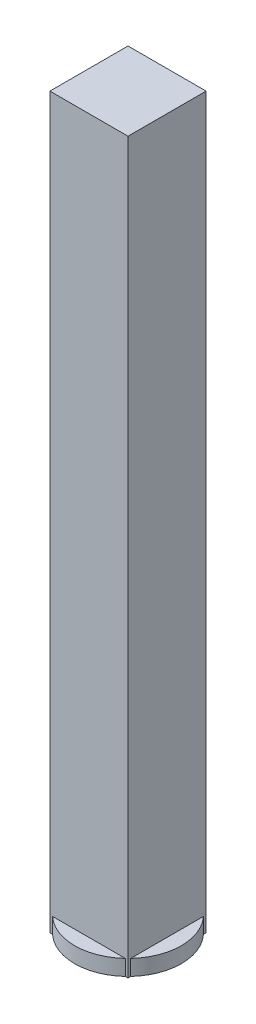
SolidWorks part; units mm, degrees
ref_plane "前视基准面" through (0, 0, 0) normal (0, 0, 1) x (1, 0, 0)
ref_plane "上视基准面" through (0, 0, 0) normal (0, 1, 0) x (1, 0, 0)
ref_plane "右视基准面" through (0, 0, 0) normal (1, 0, 0) x (0, 0, -1)
other "Configuration Table"
sketch "01_Housing_Profile" plane through (0, 0, 0) normal (0, 1, 0) x (1, 0, 0)
  line L1 (-30, -30) -> (30, -30)
  line L2 (-30, -30) -> (-30, 30)
  line L3 (-30, 30) -> (30, 30)
  line L4 (30, -30) -> (30, 30)
  line L5 (-30, -30) -> (30, 30) construction
  line L6 (-30, 30) -> (30, -30) construction
  point P0 (0, 0)
extrude "01_Housing_Block" add sketch "01_Housing_Profile" along normal blind 560
sketch "02_Face_Boss_Profile" plane through (0, 0, 0) normal (0, 1, 0) x (1, 0, 0)
  circle A0 centre (0, 0) radius 41
extrude "02_Face_Locating_Boss" add sketch "02_Face_Boss_Profile" along normal blind 12
